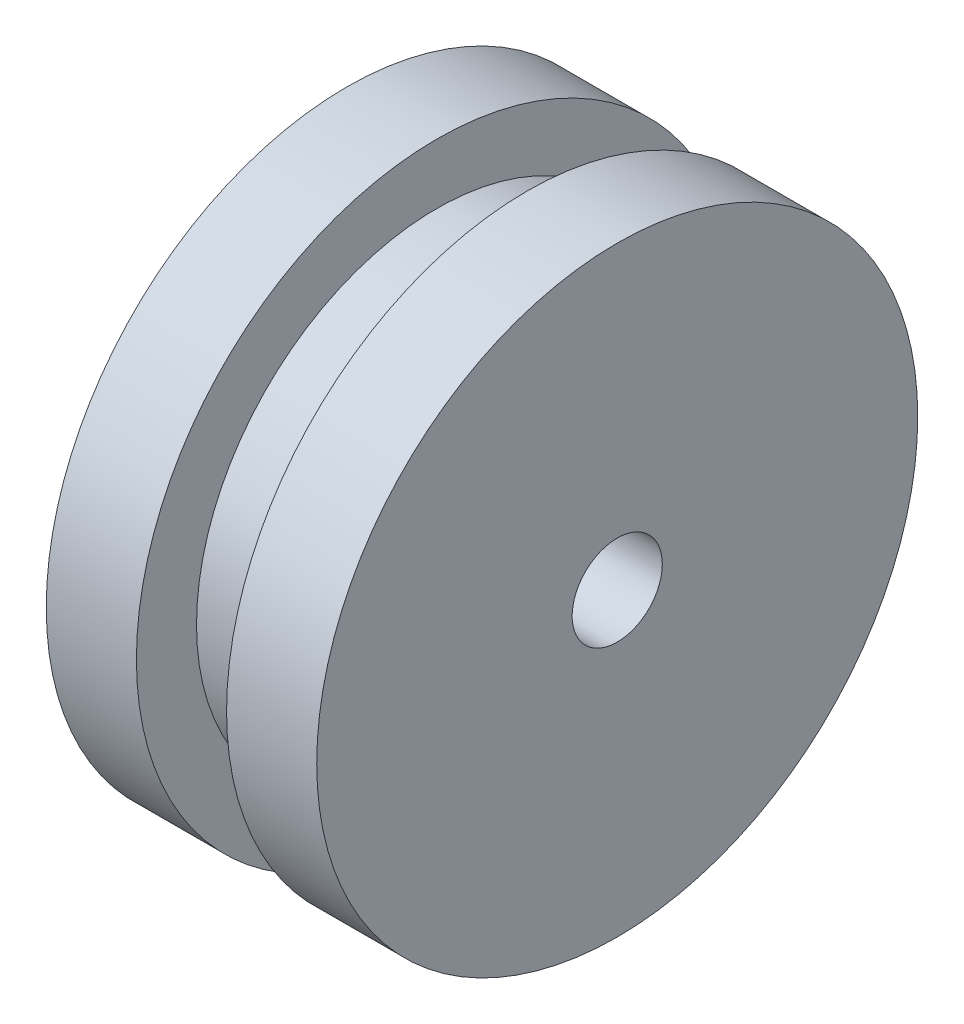
SolidWorks part; units mm, degrees
material "Corrugated Paper"
ref_plane "Front Plane" through (0, 0, 0) normal (0, 0, 1) x (1, 0, 0)
ref_plane "Top Plane" through (0, 0, 0) normal (0, 1, 0) x (1, 0, 0)
ref_plane "Right Plane" through (0, 0, 0) normal (1, 0, 0) x (0, 0, -1)
sketch "Sketch3" plane through (0, 0, 0) normal (1, 0, 0) x (0, 0, -1)
  circle A0 centre (0, 0) radius 15.875
  dimension "D1" = 31.75
extrude "Boss-Extrude1" add sketch "Sketch3" along normal blind 4.7625
sketch "Sketch5" plane through (4.7625, 0, 0) normal (1, 0, 0) x (0, 0, -1)
  circle A0 centre (0, 0) radius 12.7
  dimension "D1" = 25.4
extrude "Boss-Extrude2" add sketch "Sketch5" along normal blind 4.7625 separate body
sketch "Sketch6" plane through (9.525, 0, 0) normal (1, 0, 0) x (0, 0, -1)
  circle A0 centre (0, 0) radius 15.875 construction
  circle A1 centre (0, 0) radius 15.875
extrude "Boss-Extrude3" add sketch "Sketch6" along normal blind 4.7625 separate body
sketch "Sketch7" plane through (14.2875, 0, 0) normal (1, 0, 0) x (0, 0, -1)
  circle A0 centre (0, 0) radius 2.3813
  dimension "D1" = 4.7625
extrude "Cut-Extrude1" cut sketch "Sketch7" against normal through all
equation "\"rodThick\"= 3/16in"
equation "\"thick\"= 3/16in"
equation "\"clear\"= 0.01in"
equation "\"D1@Boss-Extrude2\"=\"thick\""
equation "\"D1@Boss-Extrude1\"=\"thick\""
equation "\"D1@Boss-Extrude3\"=\"thick\""
equation "\"D1@Sketch7\"=\"rodThick\""
